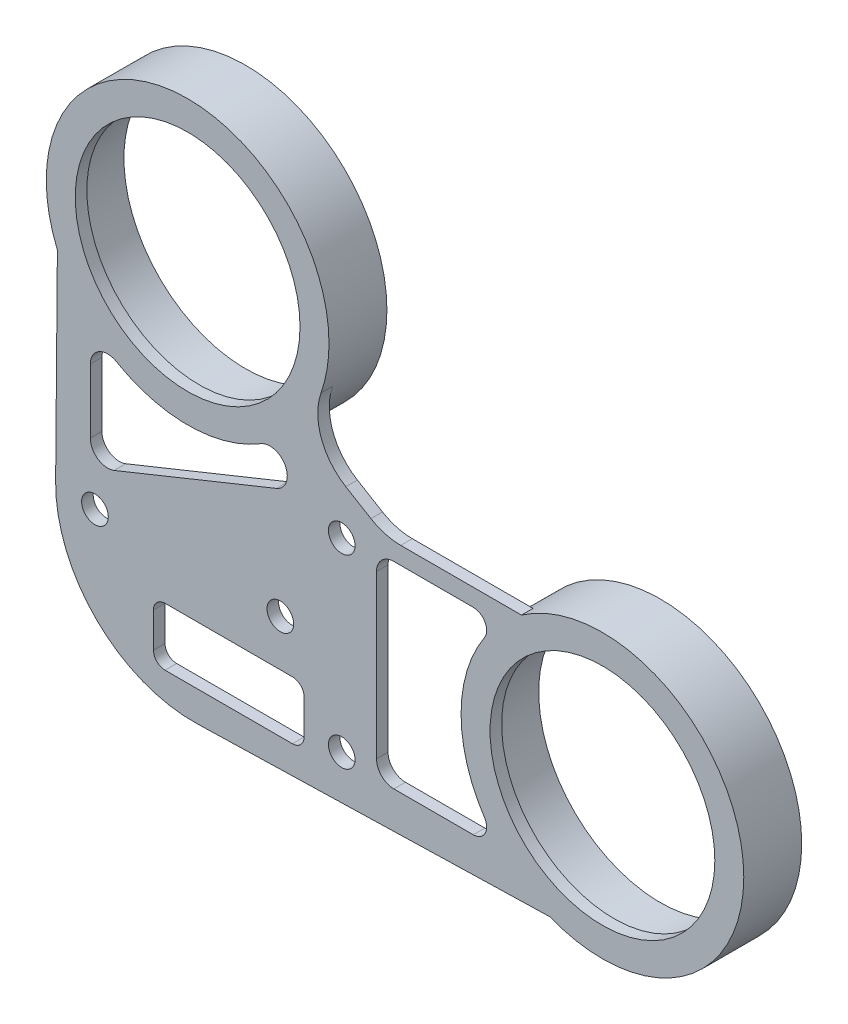
SolidWorks part; units mm, degrees
ref_plane "前视基准面" through (0, 0, 0) normal (0, 0, 1) x (1, 0, 0)
ref_plane "上视基准面" through (0, 0, 0) normal (0, 1, 0) x (1, 0, 0)
ref_plane "右视基准面" through (0, 0, 0) normal (1, 0, 0) x (0, 0, -1)
sketch "草图2" plane through (0, 0, 0) normal (0, 0, 1) x (1, 0, 0)
  line L0 (-47.9995, 22.1065) -> (-48.1935, -0.1176)
  line L1 (0.3194, -12.1958) -> (-34.9625, -13.1197)
  line L2 (-35.8, 22) -> (-35.8, 0) construction
  line L3 (-35.8, 0) -> (-0.2824, 0) construction
  line L4 (-22.1471, 12.0142) -> (-19.9836, 10.7142)
  line L5 (-17.4084, 10) -> (-6.9886, 10)
  line L6 (-48.1935, -0.1176) -> (-48.31, -13.4692) construction
  line L7 (-34.9625, -13.1197) -> (-48.31, -13.4692) construction
  line L8 (-35.8, 22) -> (0, 0) construction
  circle A0 centre (-35.8, 22) radius 9.7 construction
  circle A1 centre (0, 0) radius 9.7 construction
  arc A2 (-29.7477, 11.4071) -> (-24.2894, 17.957) centre (-35.8, 22) ccw construction
  arc A3 (0.3194, -12.1958) -> (-6.9886, 10) centre (0, 0) ccw
  arc A4 (-48.1935, -0.1176) -> (-34.9625, -13.1197) centre (-35.3, -0.2302) ccw
  arc A5 (-24.2894, 17.957) -> (-22.1471, 12.0142) centre (-19.5719, 16.3) ccw
  arc A6 (-19.9836, 10.7142) -> (-17.4084, 10) centre (-17.4084, 15) ccw
  arc A7 (-22.1471, 12.0142) -> (-24.2894, 17.957) centre (-19.5719, 16.3) ccw construction
  arc A8 (-6.9886, 10) -> (-12.2, 0) centre (0, 0) ccw construction
  circle A9 centre (0, 0) radius 12.2 construction
  arc A10 (-22.4081, 0) -> (-29.7477, 11.4071) centre (-35.3, -0.2302) ccw construction
  arc A11 (-35.8, 9.8) -> (-29.7477, 11.4071) centre (-35.8, 22) ccw construction
  circle A12 centre (-35.8, 22) radius 12.2 construction
  arc A13 (-29.7477, 11.4071) -> (-35.8, 12.6541) centre (-35.3, -0.2302) ccw construction
  arc A14 (-35.8, 12.6541) -> (-41.37, 11.1457) centre (-35.3, -0.2302) ccw construction
  arc A15 (-41.37, 11.1457) -> (-35.8, 9.8) centre (-35.8, 22) ccw construction
  arc A16 (-41.37, 11.1457) -> (-48.1935, -0.1176) centre (-35.3, -0.2302) ccw construction
  arc A17 (-24.2894, 17.957) -> (-47.9995, 22.1065) centre (-35.8, 22) ccw
  arc A18 (-34.9625, -13.1197) -> (-22.4081, 0) centre (-35.3, -0.2302) ccw construction
  arc A19 (-12.2, 0) -> (0.3194, -12.1958) centre (0, 0) ccw construction
  arc A20 (-47.9995, 22.1065) -> (-41.37, 11.1457) centre (-35.8, 22) ccw construction
  point P4 (0, 0)
  dimension "D1" = 19.4
  dimension "D7" = 35.3
  dimension "D10" = 5
  dimension "D11" = 10
  dimension "D12" = 16.3
  dimension "D2" = 35.8
  dimension "D3" = 22
  dimension "D5" = 0.5
  dimension "D6" = 1.5
  dimension "D8" = 31
  dimension "D9" = 10
  dimension "D13" = 35.8
  dimension "D4" = 2.5
extrude "凸台-拉伸1" add sketch "草图2" against normal blind 1
sketch "草图3" plane through (0, 0, 0) normal (0, 0, 1) x (1, 0, 0)
  line L0 (-19.5, 7) -> (-19.5, -7)
  line L1 (-18, -8.5) -> (-11.1445, -8.5)
  line L2 (-18, 8.5) -> (-11.1445, 8.5)
  line L3 (0, 0) -> (-22.5, 0) construction
  line L6 (-7.746, -8.5) -> (-7.7001, -8.5)
  line L7 (-44.2, 10.1645) -> (-44.2, 4.627)
  line L8 (-37.75, -4.5) -> (-26.75, -4.5)
  line L9 (-38.75, -5.5) -> (-38.75, -8.5)
  line L10 (-37.75, -9.5) -> (-26.75, -9.5)
  line L11 (-25.75, -5.5) -> (-25.75, -8.5)
  line L12 (-42.1381, 3.2362) -> (-28.1381, 8.8926)
  line L13 (-27.2, 10.2833) -> (-27.2, 11.1101) construction
  line L14 (-44.2, 14.1457) -> (-44.2, 10.1645) construction
  line L15 (-27.2, 11.1101) -> (-27.2, 14.3652) construction
  line L16 (-22.5, 8) -> (-22.5, -8) construction
  line L17 (-43.8, -0.5) -> (-27.8, -0.5) construction
  line L18 (-35.8, 22) -> (0, 0) construction
  line L19 (-35.8, -0.5) -> (-35.8, 22) construction
  circle A0 centre (0, 0) radius 9.7 construction
  circle A1 centre (-35.8, 22) radius 9.7 construction
  circle A2 centre (0, 0) radius 9.7
  circle A3 centre (-35.8, 22) radius 9.7
  arc A5 (-18, -8.5) -> (-19.5, -7) centre (-18, -7) cw
  arc A6 (-19.5, 7) -> (-18, 8.5) centre (-18, 7) cw
  arc A9 (-10.4585, 6.427) -> (-11.1445, 8.5) centre (-11.1445, 7.35) ccw
  arc A10 (-11.1445, -8.5) -> (-10.1845, -6.7169) centre (-11.1445, -7.35) ccw
  arc A11 (-10.1845, 6.7169) -> (-10.1845, -6.7169) centre (0, 0) ccw
  arc A12 (0.3194, -12.1958) -> (-6.9886, 10) centre (0, 0) ccw construction
  arc A13 (-10.1845, -6.7169) -> (-10.1845, 6.7169) centre (0, 0) ccw construction
  arc A14 (-26.75, -4.5) -> (-25.75, -5.5) centre (-26.75, -5.5) cw
  arc A15 (-25.75, -8.5) -> (-26.75, -9.5) centre (-26.75, -8.5) cw
  arc A16 (-37.75, -9.5) -> (-38.75, -8.5) centre (-37.75, -8.5) cw
  arc A17 (-38.75, -5.5) -> (-37.75, -4.5) centre (-37.75, -5.5) cw
  arc A18 (-42.1739, 12.428) -> (-29.5192, 12.3666) centre (-35.8, 22) ccw construction
  arc A19 (-24.2894, 17.957) -> (-47.9995, 22.1065) centre (-35.8, 22) ccw construction
  arc A22 (-27.2, 14.3652) -> (-44.2, 14.1457) centre (-35.8, 22) ccw construction
  arc A23 (-44.2, 14.1457) -> (-42.1739, 12.428) centre (-35.8, 22) ccw construction
  arc A24 (-29.5192, 12.3666) -> (-27.2, 14.3652) centre (-35.8, 22) ccw construction
  arc A25 (-41.9445, 11.4603) -> (-44.2, 10.1645) centre (-42.7, 10.1645) ccw
  arc A27 (-28.1381, 8.8926) -> (-27.2, 10.2833) centre (-28.7, 10.2833) ccw construction
  arc A28 (-42.1381, 3.2362) -> (-44.2, 4.627) centre (-42.7, 4.627) cw
  circle A29 centre (-43.8, -0.5) radius 1.15
  circle A30 centre (-27.8, -0.5) radius 1.15
  circle A31 centre (-22.5, 8) radius 1.15
  circle A32 centre (-22.5, -8) radius 1.15
  arc A33 (-41.9445, 11.4603) -> (-29.4774, 11.5662) centre (-35.8, 22) ccw
  arc A34 (-28.1381, 8.8926) -> (-29.4774, 11.5662) centre (-28.7, 10.2833) ccw
  arc A35 (-25.4058, 15.6125) -> (-44.2, 13.1524) centre (-35.8, 22) ccw construction
  arc A36 (-44.2, 13.1524) -> (-41.9445, 11.4603) centre (-35.8, 22) ccw construction
  arc A37 (-27.2, 13.3467) -> (-25.4058, 15.6125) centre (-35.8, 22) ccw construction
  arc A38 (-29.4774, 11.5662) -> (-27.2, 13.3467) centre (-35.8, 22) ccw construction
  arc A39 (-29.4774, 11.5662) -> (-28.1381, 8.8926) centre (-28.7, 10.2833) ccw construction
  arc A40 (-44.2, 10.1645) -> (-41.9445, 11.4603) centre (-42.7, 10.1645) ccw construction
  arc A41 (-10.1845, -6.7169) -> (-11.1445, -8.5) centre (-11.1445, -7.35) ccw construction
  arc A42 (-12.2778, 7.545) -> (-10.4585, 6.427) centre (-11.1445, 7.35) ccw construction
  arc A43 (-11.1445, 8.5) -> (-12.2778, 7.545) centre (-11.1445, 7.35) ccw construction
  point P14 (-19.5, -8.5)
  point P17 (-19.5, 8.5)
  point P30 (-25.75, -4.5)
  point P33 (-25.75, -9.5)
  point P38 (-38.75, -4.5)
  point P47 (-27.2, 9.2716)
  dimension "D4" = 1.5
  dimension "D10" = 1
  dimension "D11" = 23
  dimension "D18" = 1.5
  dimension "D19" = 2.3
  dimension "D2" = 17
  dimension "D3" = 19.5
  dimension "D6" = 25.75
  dimension "D7" = 9.5
  dimension "D8" = 5
  dimension "D9" = 13
  dimension "D12" = 68
  dimension "D13" = 44.2
  dimension "D14" = 27.2
  dimension "D20" = 16
  dimension "D22" = 22.5
  dimension "D23" = 22.5
  dimension "D24" = 16
extrude "切除-拉伸1" cut sketch "草图3" against normal through all
sketch "草图4" plane through (0, 0, -1) normal (0, 0, 1) x (1, 0, 0)
  circle A0 centre (-35.8, 22) radius 10.5
  circle A1 centre (-35.8, 22) radius 12.2
  arc A2 (-24.2894, 17.957) -> (-47.9995, 22.1065) centre (-35.8, 22) ccw construction
  circle A3 centre (0, 0) radius 10.5
  circle A4 centre (0, 0) radius 12.2
  arc A5 (0.3194, -12.1958) -> (-6.9886, 10) centre (0, 0) ccw construction
  dimension "D1" = 21
extrude "凸台-拉伸2" add sketch "草图4" against normal blind 4
sketch "草图6" plane through (0, 0, -1) normal (0, 0, -1) x (-1, 0, 0)
  line L0 (47.9995, 22.1065) -> (48.1935, -0.1176) construction
  line L1 (34.9625, -13.1197) -> (-0.3194, -12.1958) construction
  line L2 (47.9995, 22.1065) -> (48.1935, -0.1176)
  line L3 (34.9625, -13.1197) -> (-0.3194, -12.1958)
  line L4 (34.9887, -12.12) -> (4.5425, -11.3228)
  line L5 (47.1935, -0.1264) -> (47.0418, 17.2606)
  line L6 (47.0605, 15.1123) -> (47.1935, -0.1264) construction
  line L7 (34.9887, -12.12) -> (6.6901, -11.379) construction
  arc A0 (-0.3194, -12.1958) -> (10.1845, -6.7169) centre (0, 0) ccw construction
  arc A1 (41.9445, 11.4603) -> (47.9995, 22.1065) centre (35.8, 22) ccw construction
  arc A2 (-0.3194, -12.1958) -> (4.5425, -11.3228) centre (0, 0) ccw
  arc A3 (47.0418, 17.2606) -> (47.9995, 22.1065) centre (35.8, 22) ccw
  arc A4 (34.9625, -13.1197) -> (48.1935, -0.1176) centre (35.3, -0.2302) ccw construction
  arc A5 (34.9625, -13.1197) -> (48.1935, -0.1176) centre (35.3, -0.2302) ccw
  circle A6 centre (0, 0) radius 12.2 construction
  arc A7 (34.9887, -12.12) -> (47.1935, -0.1264) centre (35.3, -0.2302) ccw
  arc A8 (-0.3194, -12.1958) -> (10.1845, -6.7169) centre (0, 0) ccw construction
  arc A9 (6.6901, -11.379) -> (11.0193, -7.2674) centre (0, 0) ccw construction
  arc A10 (42.4482, 10.5964) -> (47.0605, 15.1123) centre (35.8, 22) ccw construction
  arc A11 (41.9445, 11.4603) -> (47.9995, 22.1065) centre (35.8, 22) ccw construction
  dimension "D1" = 1
extrude "切除-拉伸2" cut sketch "草图6" against normal through all
